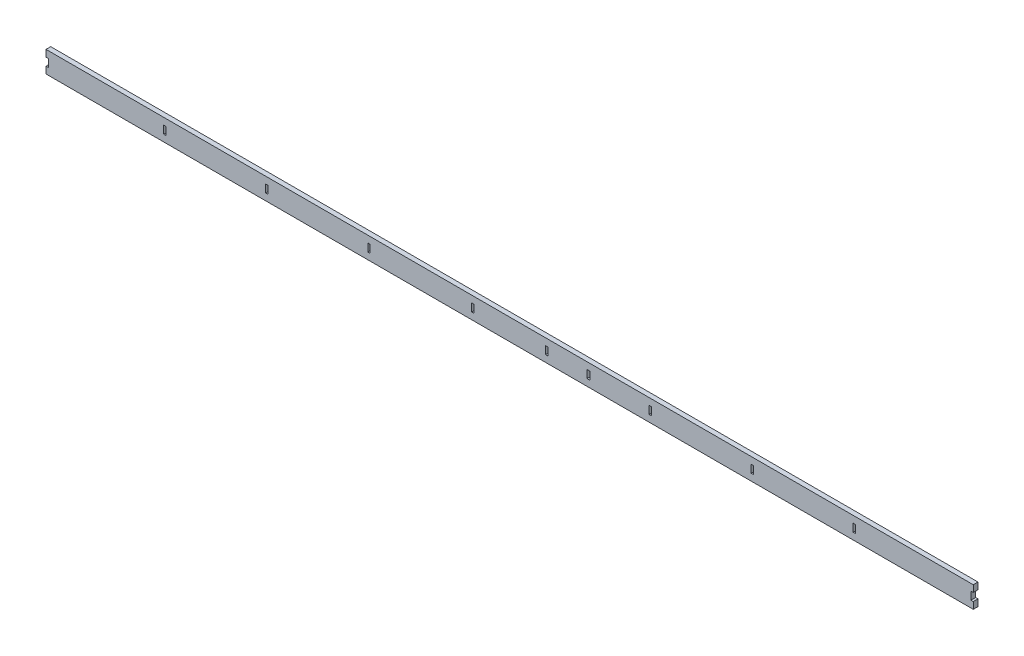
SolidWorks part; units mm, degrees
ref_plane "前视基准面" through (0, 0, 0) normal (0, 0, 1) x (1, 0, 0)
ref_plane "上视基准面" through (0, 0, 0) normal (0, 1, 0) x (1, 0, 0)
ref_plane "右视基准面" through (0, 0, 0) normal (1, 0, 0) x (0, 0, -1)
sketch "Model" plane through (0, 0, 0) normal (0, 0, 1) x (1, 0, 0)
  line L0 (575.2405, 18.8797) -> (-15.5558, 18.8797)
  line L1 (-15.5558, 18.8797) -> (-15.5558, 14.5797)
  line L2 (-15.5558, 9.5797) -> (-15.5558, 5.2797)
  line L3 (-15.5558, 5.2797) -> (575.2405, 5.2797)
  line L4 (575.2405, 18.8797) -> (575.2405, 14.5797)
  line L5 (575.2405, 9.5797) -> (575.2405, 5.2797)
  line L6 (575.2405, 14.5797) -> (573.7405, 14.5797)
  line L7 (573.7405, 14.5797) -> (573.7405, 9.5797)
  line L8 (573.7405, 9.5797) -> (575.2405, 9.5797)
  line L9 (573.7405, 14.5797) -> (573.7405, 12.0797)
  line L10 (-15.5558, 14.5797) -> (-14.0558, 14.5797)
  line L11 (-14.0558, 14.5797) -> (-14.0558, 9.5797)
  line L12 (-14.0558, 9.5797) -> (-15.5558, 9.5797)
  line L13 (329.1441, 14.5797) -> (329.1441, 9.5797)
  line L14 (331.1441, 14.5797) -> (331.1441, 9.5797)
  line L15 (331.1441, 9.5797) -> (329.1441, 9.5797)
  line L16 (331.1441, 14.5797) -> (329.1441, 14.5797)
  line L17 (59.4442, 12.0797) -> (59.4442, 14.5797)
  line L18 (59.4442, 14.5797) -> (60.9442, 14.5797)
  line L19 (60.9442, 14.5797) -> (60.9442, 9.5797)
  line L20 (60.9442, 9.5797) -> (59.4442, 9.5797)
  line L21 (59.4442, 9.5797) -> (59.4442, 12.0797)
  line L22 (124.4442, 12.0797) -> (124.4442, 14.5797)
  line L23 (124.4442, 14.5797) -> (125.9442, 14.5797)
  line L24 (125.9442, 14.5797) -> (125.9442, 9.5797)
  line L25 (125.9442, 9.5797) -> (124.4442, 9.5797)
  line L26 (124.4442, 9.5797) -> (124.4442, 12.0797)
  line L27 (189.4442, 12.0797) -> (189.4442, 14.5797)
  line L28 (189.4442, 14.5797) -> (190.9442, 14.5797)
  line L29 (190.9442, 14.5797) -> (190.9442, 9.5797)
  line L30 (190.9442, 9.5797) -> (189.4442, 9.5797)
  line L31 (189.4442, 9.5797) -> (189.4442, 12.0797)
  line L32 (255.6441, 12.0797) -> (255.6441, 14.5797)
  line L33 (255.6441, 14.5797) -> (257.1441, 14.5797)
  line L34 (257.1441, 14.5797) -> (257.1441, 9.5797)
  line L35 (257.1441, 9.5797) -> (255.6441, 9.5797)
  line L36 (255.6441, 9.5797) -> (255.6441, 12.0797)
  line L37 (302.6441, 12.0797) -> (302.6441, 14.5797)
  line L38 (302.6441, 14.5797) -> (304.1441, 14.5797)
  line L39 (304.1441, 14.5797) -> (304.1441, 9.5797)
  line L40 (304.1441, 9.5797) -> (302.6441, 9.5797)
  line L41 (302.6441, 9.5797) -> (302.6441, 12.0797)
  line L42 (368.7405, 12.0797) -> (368.7405, 14.5797)
  line L43 (368.7405, 14.5797) -> (370.2405, 14.5797)
  line L44 (370.2405, 14.5797) -> (370.2405, 9.5797)
  line L45 (370.2405, 9.5797) -> (368.7405, 9.5797)
  line L46 (368.7405, 9.5797) -> (368.7405, 12.0797)
  line L47 (433.7405, 12.0797) -> (433.7405, 14.5797)
  line L48 (433.7405, 14.5797) -> (435.2405, 14.5797)
  line L49 (435.2405, 14.5797) -> (435.2405, 9.5797)
  line L50 (435.2405, 9.5797) -> (433.7405, 9.5797)
  line L51 (433.7405, 9.5797) -> (433.7405, 12.0797)
  line L52 (498.7405, 12.0797) -> (498.7405, 14.5797)
  line L53 (498.7405, 14.5797) -> (500.2405, 14.5797)
  line L54 (500.2405, 14.5797) -> (500.2405, 9.5797)
  line L55 (500.2405, 9.5797) -> (498.7405, 9.5797)
  line L56 (498.7405, 9.5797) -> (498.7405, 12.0797)
extrude "凸台-拉伸2" add sketch "Model" along normal blind 3 contours L11 L12 L2 L3 L5 L8 L7 L6 L4 L0 L1 L10 L16 L14 L15 L13 L20 L21 L17 L18 L19 L25 L26 L22 L23 L24 L30 L31 L27 L28 L29 L35 L36 L32 L33 L34 L40 L41 L37 L38 L39 L45 L46
